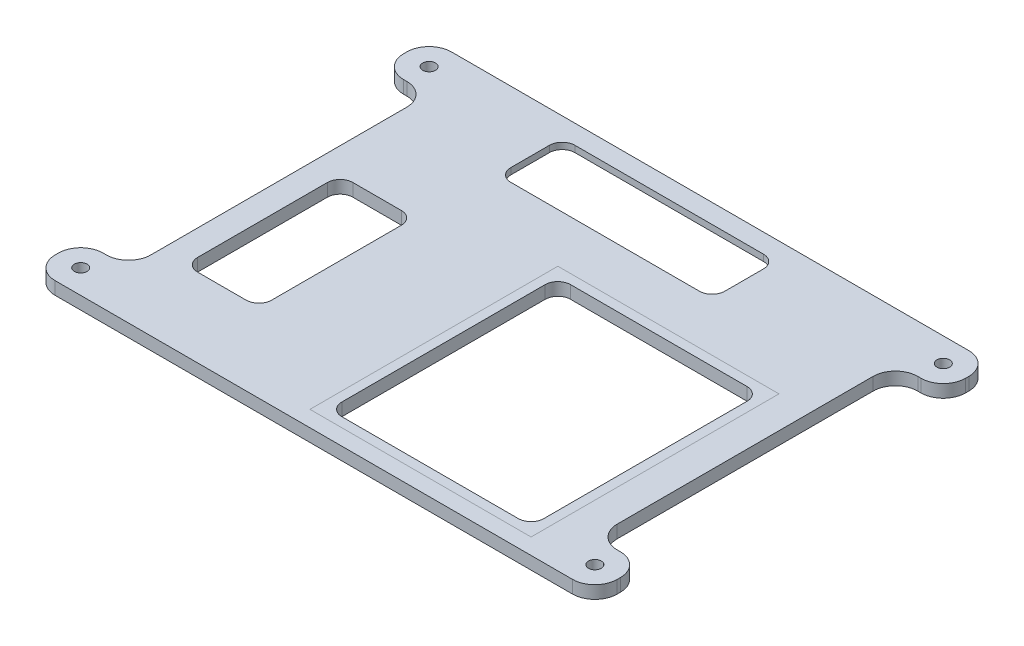
SolidWorks part; units mm, degrees
ref_plane "Front Plane" through (0, 0, 0) normal (0, 0, 1) x (1, 0, 0)
ref_plane "Top Plane" through (0, 0, 0) normal (0, 1, 0) x (1, 0, 0)
ref_plane "Right Plane" through (0, 0, 0) normal (1, 0, 0) x (0, 0, -1)
sketch "Sketch1" plane through (0, 0, 0) normal (0, 1, 0) x (1, 0, 0)
  line L0 (0, 77.7) -> (0, 91.1)
  line L1 (0, 0) -> (-69.3, 0)
  line L2 (0, 0) -> (0, 77.7)
  line L3 (0, 77.7) -> (-69.3, 77.7)
  line L4 (-69.3, 0) -> (-69.3, 77.7)
  line L5 (0, 91.1) -> (-34.35, 91.1)
  line L6 (-34.35, 91.1) -> (-34.35, 115.2)
  line L7 (-34.35, 115.2) -> (-105.45, 115.2)
  line L8 (-105.45, 115.2) -> (-105.45, 91.1)
  line L9 (-105.45, 91.1) -> (-34.35, 91.1)
  line L10 (-105.45, 91.1) -> (-105.45, 64.3)
  line L11 (-105.45, 64.3) -> (-108.95, 64.3)
  line L12 (-108.95, 64.3) -> (-108.95, 23.64)
  line L13 (-108.95, 23.64) -> (-124.15, 23.64)
  line L14 (-124.15, 23.64) -> (-124.15, 64.3)
  line L15 (-124.15, 64.3) -> (-108.95, 64.3)
  line L16 (0, 0) -> (20, 0) construction
  line L17 (20, 0) -> (20, -10) construction
  line L18 (-105.45, 115.2) -> (-105.45, 125.2) construction
  line L19 (-124.15, 64.3) -> (-144.15, 64.3) construction
  line L20 (-144.15, 64.3) -> (-144.15, 125.2) construction
  line L21 (-144.15, 125.2) -> (-105.45, 125.2) construction
  line L23 (-144.15, 125.2) -> (20, 125.2)
  line L24 (-144.15, 125.2) -> (-144.15, -10)
  line L25 (-144.15, -10) -> (20, -10)
  line L26 (20, 125.2) -> (20, -10)
  dimension "D1" = 20
extrude "Boss-Extrude1" add sketch "Sketch1" along normal blind 4
sketch "Sketch3" plane through (0, 4, 0) normal (0, 1, 0) x (1, 0, 0)
  line L1 (-105.45, 115.2) -> (-34.35, 115.2)
  line L2 (-105.45, 115.2) -> (-105.45, 91.1)
  line L3 (-105.45, 91.1) -> (-34.35, 91.1)
  line L4 (-34.35, 115.2) -> (-34.35, 91.1)
extrude "Extrude-Thin1" add sketch "Sketch3" against normal blind 2 thin thin type mid plane wall 4
sketch "Sketch4" plane through (0, 4, 0) normal (0, 1, 0) x (1, 0, 0)
  line L1 (-124.15, 64.3) -> (-108.95, 64.3)
  line L2 (-124.15, 64.3) -> (-124.15, 23.64)
  line L3 (-124.15, 23.64) -> (-108.95, 23.64)
  line L4 (-108.95, 64.3) -> (-108.95, 23.64)
extrude "Cut-Extrude-Thin1" cut sketch "Sketch4" against normal blind 10 thin thin type one direction wall 4
sketch "Sketch8" plane through (0, 4, 0) normal (0, 1, 0) x (1, 0, 0)
  line L0 (20, 125.2) -> (20, -10) construction
  line L1 (-144.15, 125.2) -> (20, 125.2)
  line L2 (-144.15, 125.2) -> (-144.15, 119.2)
  line L3 (-144.15, 119.2) -> (20, 119.2)
  line L4 (20, 125.2) -> (20, 119.2)
  line L5 (-128.15, 68.3) -> (-136.15, 68.3)
  line L6 (-144.15, -10) -> (20, -10)
  line L7 (-144.15, -10) -> (-144.15, -5)
  line L8 (-144.15, -5) -> (20, -5)
  line L9 (20, -10) -> (20, -5)
  line L10 (0, 77.7) -> (10, 77.7)
  line L11 (-144.15, 119.2) -> (-136.15, 119.2)
  line L12 (-144.15, 119.2) -> (-144.15, -5)
  line L13 (-144.15, -5) -> (-136.15, -5)
  line L14 (-136.15, 119.2) -> (-136.15, -5)
  line L16 (20, 119.2) -> (10, 119.2)
  line L17 (20, 119.2) -> (20, -5)
  line L18 (20, -5) -> (10, -5)
  line L19 (10, 119.2) -> (10, -5)
  line M14 (20, -10) -> (20, 125.2)
  line M15 (20, 125.2) -> (-144.15, 125.2)
  line M16 (-144.15, 125.2) -> (-144.15, -10)
  line M17 (-144.15, -10) -> (20, -10)
extrude "Cut-Extrude4" cut sketch "Sketch8" against normal blind 4 contours L14 L3 L8 M16 | L3 L19 L8 M14 | L8 M16 M17 M14 | L3 M16 M14 M15
fillet "Fillet3" radius 4 8 edges at (-128.15, 2, -68.3) (-104.95, 2, -68.3) (-104.95, 2, -19.64) (-128.15, 2, -19.64) (-103.45, 3, -93.1) (-36.35, 3, -93.1) (-36.35, 3, -113.2) (-103.45, 3, -113.2)
sketch "Sketch9" plane through (0, 4, 0) normal (0, 1, 0) x (1, 0, 0)
  line L0 (-63.075, 119.2) -> (-63.075, -5) construction
  line L1 (-136.15, 119.2) -> (-151.15, 119.2)
  line L2 (-136.15, 119.2) -> (-136.15, 104.2)
  line L3 (-136.15, 104.2) -> (-151.15, 104.2)
  line L4 (-151.15, 119.2) -> (-151.15, 104.2)
  line L5 (-136.15, 119.2) -> (10, 119.2) construction
  line L6 (-136.15, -5) -> (10, -5) construction
  line L7 (-63.075, -5) -> (-136.15, 57.1) construction
  line L8 (-136.15, 119.2) -> (-136.15, -5) construction
  line L9 (-136.15, 57.1) -> (10, 57.1) construction
  line L10 (10, 119.2) -> (10, -5) construction
  line L11 (25, 119.2) -> (25, 104.2)
  line L12 (10, 104.2) -> (25, 104.2)
  line L13 (10, 119.2) -> (10, 104.2)
  line L14 (10, 119.2) -> (25, 119.2)
  line L15 (10, -5) -> (25, -5)
  line L16 (10, -5) -> (10, 10)
  line L17 (10, 10) -> (25, 10)
  line L18 (25, -5) -> (25, 10)
  line L19 (-151.15, -5) -> (-151.15, 10)
  line L20 (-136.15, 10) -> (-151.15, 10)
  line L21 (-136.15, -5) -> (-136.15, 10)
  line L22 (-136.15, -5) -> (-151.15, -5)
  circle A0 centre (-143.65, 111.7) radius 2
  circle A1 centre (17.5, 111.7) radius 2
  circle A2 centre (17.5, 2.5) radius 2
  circle A3 centre (-143.65, 2.5) radius 2
extrude "Boss-Extrude5" add sketch "Sketch9" against normal blind 4
fillet "Fillet4" radius 7 12 edges at (25, 2, -119.2) (25, 2, -104.2) (10, 2, -104.2) (10, 2, -10) (25, 2, -10) (25, 2, 5) (-136.15, 2, -10) (-151.15, 2, 5) (-151.15, 2, -10) (-136.15, 2, -104.2) (-151.15, 2, -104.2) (-151.15, 2, -119.2)
sketch "Sketch10" plane through (0, 4, 0) normal (0, 1, 0) x (1, 0, 0)
  line L1 (-69.3, 77.7) -> (0, 77.7)
  line L2 (-69.3, 77.7) -> (-69.3, 0)
  line L3 (-69.3, 0) -> (0, 0)
  line L4 (0, 77.7) -> (0, 0)
extrude "Extrude-Thin2" add sketch "Sketch10" against normal blind 4 separate body thin
fillet "Fillet5" radius 4 4 edges at (-66.3, 2, -3) (-3, 2, -3) (-3, 2, -74.7) (-66.3, 2, -74.7)
